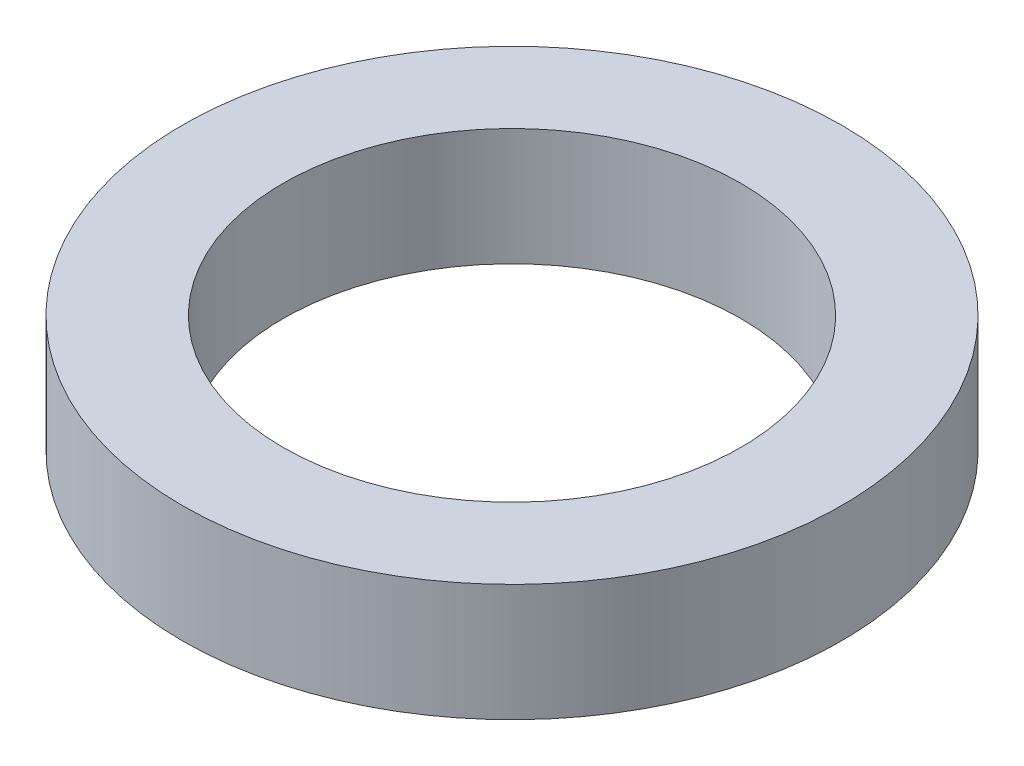
SolidWorks part; units mm, degrees
ref_plane "Front Plane" through (0, 0, 0) normal (0, 0, 1) x (1, 0, 0)
ref_plane "Top Plane" through (0, 0, 0) normal (0, 1, 0) x (1, 0, 0)
ref_plane "Right Plane" through (0, 0, 0) normal (1, 0, 0) x (0, 0, -1)
sketch "Sketch1" plane through (0, 0, 0) normal (0, 1, 0) x (1, 0, 0)
  circle A0 centre (0, 0) radius 2.286
  dimension "OD" = 4.572
extrude "Boss-Extrude1" add sketch "Sketch1" along normal blind 0.8128
sketch "Sketch5" plane through (0, 0.8128, 0) normal (0, 1, 0) x (-1, 0, 0)
  circle A0 centre (0, 0) radius 1.5875
  dimension "ID" = 3.175
extrude "Cut-Extrude1" cut sketch "Sketch5" against normal through all
